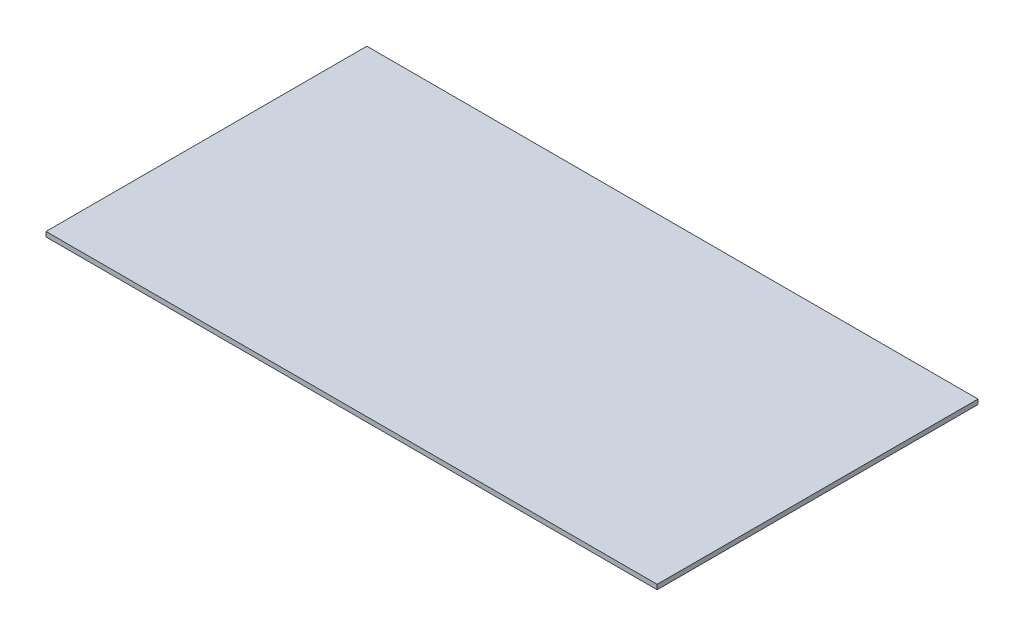
SolidWorks part; units mm, degrees
ref_plane "Front Plane" through (0, 0, 0) normal (0, 0, 1) x (1, 0, 0)
ref_plane "Top Plane" through (0, 0, 0) normal (0, 1, 0) x (1, 0, 0)
ref_plane "Right Plane" through (0, 0, 0) normal (1, 0, 0) x (0, 0, -1)
sketch "Sketch1" plane through (0, 0, 0) normal (0, 1, 0) x (1, 0, 0)
  line L1 (-26.7629, 18.9979) -> (5.2371, 18.9979)
  line L2 (-26.7629, 18.9979) -> (-26.7629, 2.1979)
  line L3 (-26.7629, 2.1979) -> (5.2371, 2.1979)
  line L4 (5.2371, 18.9979) -> (5.2371, 2.1979)
  dimension "D1" = 16.8
  dimension "D2" = 32
extrude "Boss-Extrude1" add sketch "Sketch1" along normal blind 0.25
